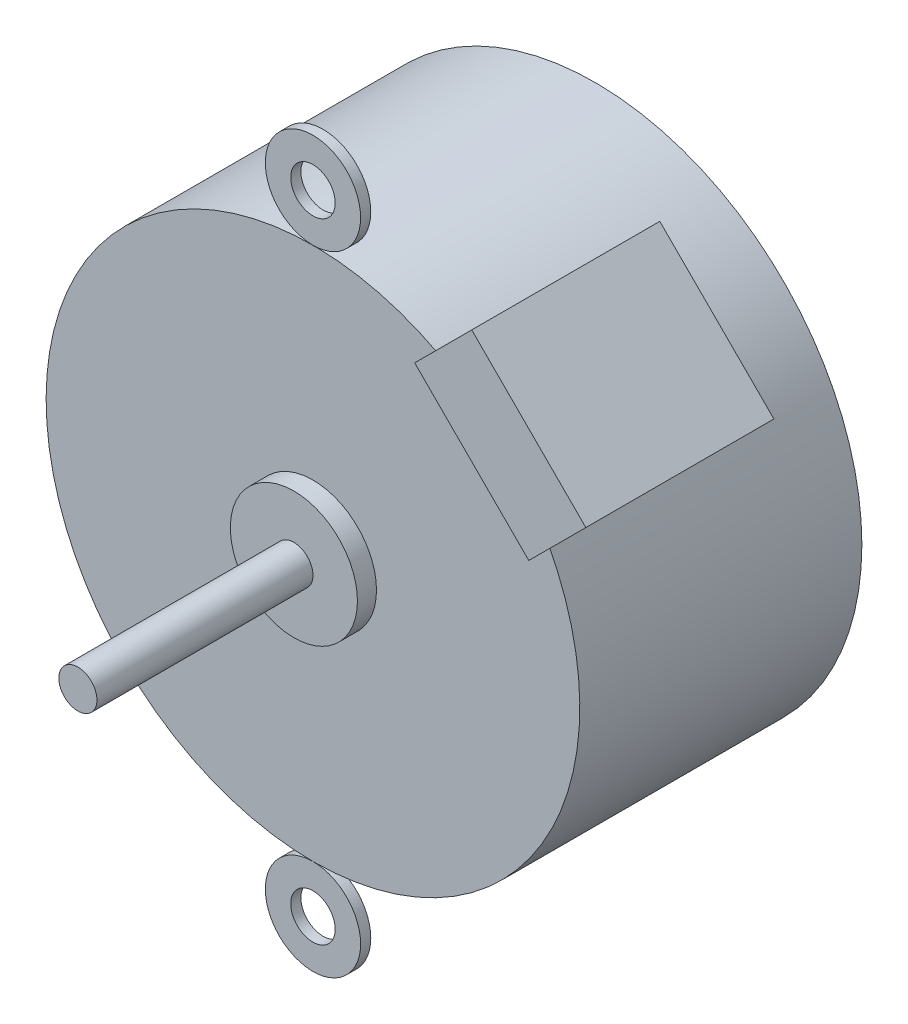
SolidWorks part; units mm, degrees
ref_plane "Front Plane" through (0, 0, 0) normal (0, 0, 1) x (1, 0, 0)
ref_plane "Top Plane" through (0, 0, 0) normal (0, 1, 0) x (1, 0, 0)
ref_plane "Right Plane" through (0, 0, 0) normal (1, 0, 0) x (0, 0, -1)
sketch "Sketch1" plane through (0, 0, 0) normal (0, 0, 1) x (1, 0, 0)
  circle A0 centre (0, 0) radius 21
extrude "Boss-Extrude1" add sketch "Sketch1" along normal blind 0.8
sketch "Sketch2" plane through (0, 0, 0) normal (0, 0, 1) x (1, 0, 0)
  circle A0 centre (0, 24.75) radius 3.75
extrude "Boss-Extrude2" add sketch "Sketch2" along normal blind 0.8
sketch "Sketch3" plane through (0, 0, 0) normal (0, 0, 1) x (1, 0, 0)
  circle A0 centre (0, -24.75) radius 3.75
extrude "Boss-Extrude3" add sketch "Sketch3" along normal blind 0.8
sketch "Sketch4" plane through (0, 0, 0) normal (0, 0, 1) x (1, 0, 0)
  circle A0 centre (0, 24.75) radius 1.75
  circle A1 centre (0, -24.75) radius 1.75
extrude "Cut-Extrude2" cut sketch "Sketch4" along normal blind 1.8
sketch "Sketch5" plane through (0, 0, 0) normal (0, 0, 1) x (1, 0, 0)
  circle A0 centre (0, 0) radius 21
extrude "Boss-Extrude4" add sketch "Sketch5" against normal blind 21.4
sketch "Sketch6" plane through (0, 0, 0) normal (0, 0, 1) x (1, 0, 0)
  circle A0 centre (0, 0) radius 4
extrude "Boss-Extrude5" add sketch "Sketch6" against normal blind 22.4
sketch "Sketch7" plane through (0, 0, 0) normal (0, 0, 1) x (1, 0, 0)
  circle A0 centre (0, 0) radius 5
extrude "Boss-Extrude6" add sketch "Sketch7" along normal blind 2.3
sketch "Sketch8" plane through (0, 0, 0) normal (0, 0, 1) x (1, 0, 0)
  circle A0 centre (0, 0) radius 1.5
extrude "Boss-Extrude7" add sketch "Sketch8" along normal blind 19.3
sketch "Sketch9" plane through (0, 0, 0) normal (0, 0, 1) x (1, 0, 0)
  line L0 (18.9858, 10.0056) -> (10.0056, 18.9858)
  line L1 (10.0056, 18.9858) -> (14.4957, 23.4759)
  line L2 (14.4957, 23.4759) -> (23.4759, 14.4957)
  line L3 (23.4759, 14.4957) -> (18.9858, 10.0056)
extrude "Boss-Extrude8" add sketch "Sketch9" against normal blind 12
sketch "Sketch10" plane through (0, 0, 0) normal (0, 0, 1) x (1, 0, 0)
  line L0 (18.9858, 10.0056) -> (10.0056, 18.9858)
  line L1 (10.0056, 18.9858) -> (14.4957, 23.4759)
  line L2 (14.4957, 23.4759) -> (10.0056, 18.9858) construction
  line L3 (14.4957, 23.4759) -> (23.4759, 14.4957)
  line L4 (18.9858, 10.0056) -> (23.4759, 14.4957) construction
  line L5 (23.4759, 14.4957) -> (18.9858, 10.0056)
extrude "Boss-Extrude9" add sketch "Sketch10" along normal blind 2.8
